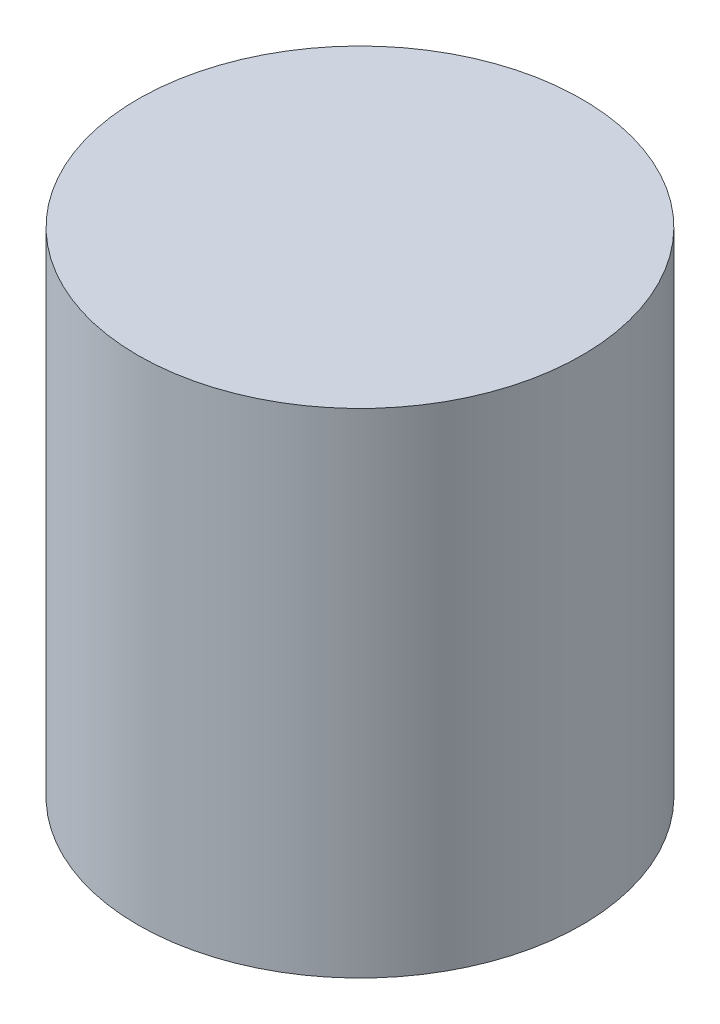
SolidWorks part; units mm, degrees
ref_plane "Front Plane" through (0, 0, 0) normal (0, 0, 1) x (1, 0, 0)
ref_plane "Top Plane" through (0, 0, 0) normal (0, 1, 0) x (1, 0, 0)
ref_plane "Right Plane" through (0, 0, 0) normal (1, 0, 0) x (0, 0, -1)
sketch "Sketch1" plane through (0, 0, 0) normal (0, 1, 0) x (1, 0, 0)
  circle A0 centre (0, 0) radius 9
  dimension "D1" = 18
extrude "Boss-Extrude1" add sketch "Sketch1" along normal blind 20
